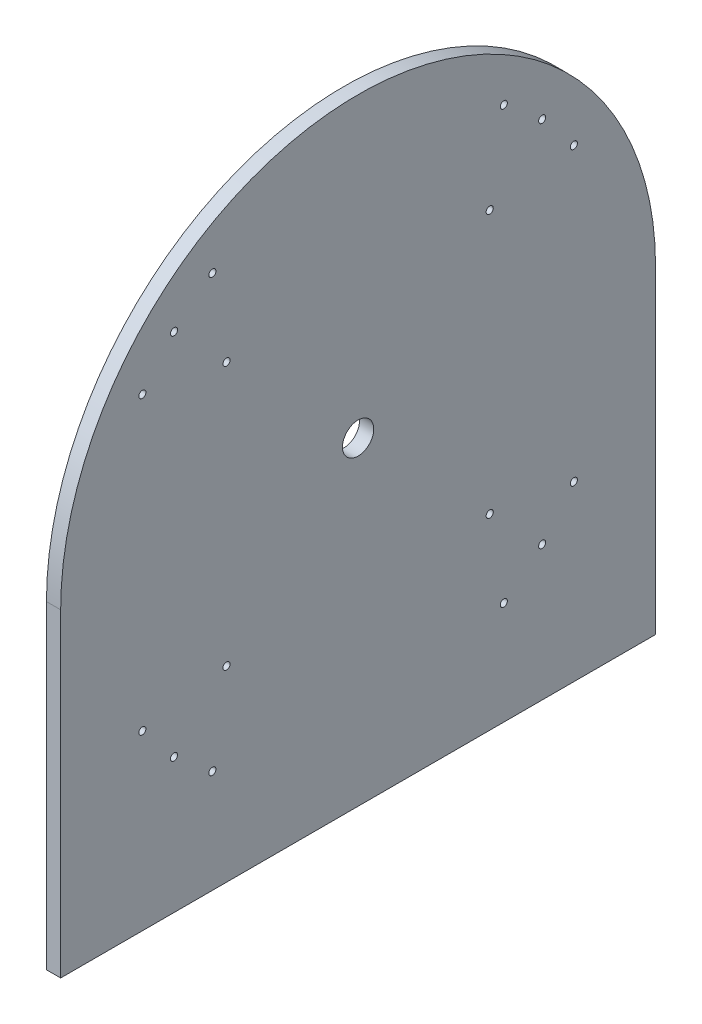
SolidWorks part; units mm, degrees
ref_plane "Front Plane" through (0, 0, 0) normal (0, 0, 1) x (1, 0, 0)
ref_plane "Top Plane" through (0, 0, 0) normal (0, 1, 0) x (1, 0, 0)
ref_plane "Right Plane" through (0, 0, 0) normal (1, 0, 0) x (0, 0, -1)
sketch "Sketch1" plane through (0, 0, 0) normal (1, 0, 0) x (0, 0, -1)
  line L1 (209.31, -224.4) -> (-209.31, -224.4)
  line L2 (209.31, -224.4) -> (209.31, 0)
  line L3 (209.31, 0) -> (-209.31, 0)
  line L4 (-209.31, -224.4) -> (-209.31, 0)
  line L5 (209.31, -224.4) -> (-209.31, 0) construction
  line L6 (209.31, 0) -> (-209.31, -224.4) construction
  circle A0 centre (0, 0) radius 209.31
  point P2 (0, -112.2)
  dimension "D1" = 418.62
  dimension "D2" = 224.4
extrude "Boss-Extrude1" add sketch "Sketch1" along normal blind 10 contours L3 A0 | L3 A0 | A0 L4 L1 L2
sketch "Sketch2" plane through (10, 0, 0) normal (1, 0, 0) x (0, 0, -1)
  line L0 (116.7928, 116.7928) -> (0, 0) construction
  line L1 (0, 0) -> (0, 165.17) construction
  line L2 (92.6098, 92.6098) -> (129.5349, 129.5349)
  circle A0 centre (0, 0) radius 165.17
  circle A3 centre (0, 0) radius 157.08
  circle A4 centre (129.5349, 129.5349) radius 2.5
  circle A5 centre (92.6098, 92.6098) radius 2.5
  circle A6 centre (92.6098, -92.6098) radius 2.5
  circle A7 centre (129.5349, -129.5349) radius 2.5
  circle A8 centre (-92.6098, -92.6098) radius 2.5
  circle A9 centre (-129.5349, -129.5349) radius 2.5
  circle A10 centre (-92.6098, 92.6098) radius 2.5
  circle A11 centre (-129.5349, 129.5349) radius 2.5
  point P9 (111.0723, 111.0723)
  point P10 (153.2003, 34.6957)
  dimension "D1" = 330.34
  dimension "D3" = 52.22
  dimension "D4" = 8.09
  dimension "D5" = 5
  dimension "D6" = 5
  dimension "D2" = 45
  dimension "D7" = 4
extrude "Cut-Extrude1" cut sketch "Sketch2" against normal blind 10
sketch "Sketch3" plane through (10, 0, 0) normal (1, 0, 0) x (0, 0, -1)
  circle A0 centre (0, 0) radius 11
  dimension "D1" = 22
extrude "Cut-Extrude2" cut sketch "Sketch3" against normal blind 10
sketch "Sketch4" plane through (10, 0, 0) normal (1, 0, 0) x (0, 0, -1)
  line L0 (-129.5349, 129.5349) -> (-92.6098, 92.6098) construction
  circle A1 centre (-151.8062, 102.5351) radius 2.5
  circle A2 centre (-129.5349, 129.5349) radius 2.5 construction
  circle A3 centre (-102.5351, 151.8062) radius 2.5
  circle A4 centre (102.5351, 151.8062) radius 2.5
  circle A5 centre (151.8062, 102.5351) radius 2.5
  circle A6 centre (151.8062, -102.5351) radius 2.5
  circle A7 centre (102.5351, -151.8062) radius 2.5
  circle A8 centre (-102.5351, -151.8062) radius 2.5
  circle A9 centre (-151.8062, -102.5351) radius 2.5
  dimension "D1" = 5
  dimension "D2" = 35
  dimension "D3" = 4
extrude "Cut-Extrude3" cut sketch "Sketch4" against normal blind 10
